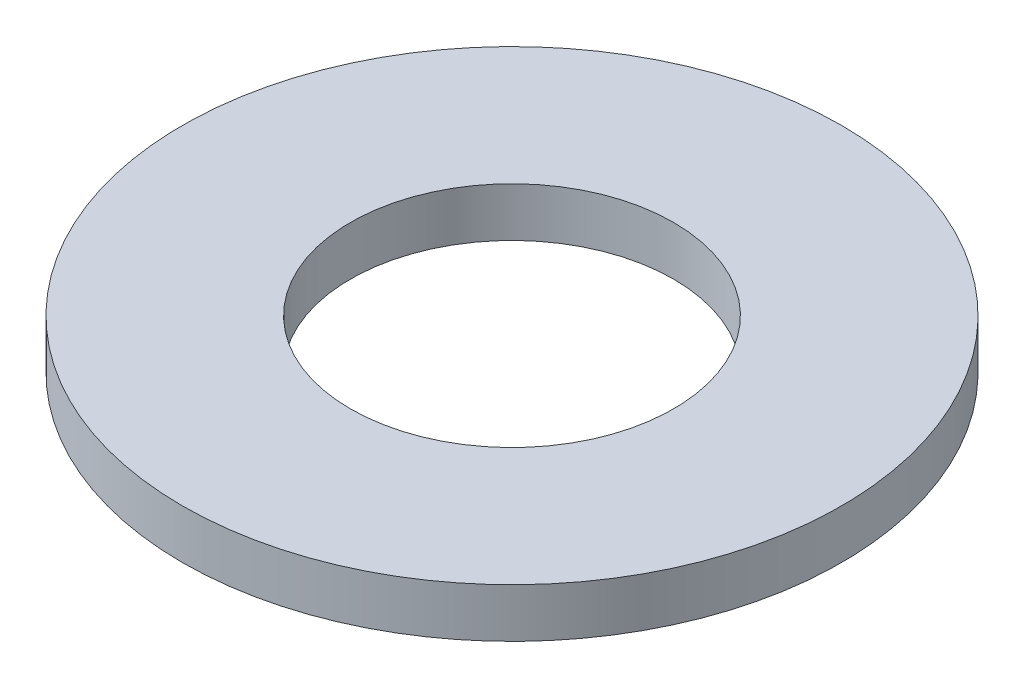
SolidWorks part; units mm, degrees
ref_plane "Front Plane" through (0, 0, 0) normal (0, 0, 1) x (1, 0, 0)
ref_plane "Top Plane" through (0, 0, 0) normal (0, 1, 0) x (1, 0, 0)
ref_plane "Right Plane" through (0, 0, 0) normal (1, 0, 0) x (0, 0, -1)
sketch "Sketch1" plane through (0, 0, 0) normal (0, 1, 0) x (1, 0, 0)
  circle A0 centre (0, 0) radius 3.2385
  dimension "OD" = 6.477
extrude "Boss-Extrude1" add sketch "Sketch1" along normal blind 0.4826
sketch "Sketch5" plane through (0, 0.4826, 0) normal (0, 1, 0) x (-1, 0, 0)
  circle A0 centre (0, 0) radius 1.5875
  dimension "ID" = 3.175
extrude "Cut-Extrude1" cut sketch "Sketch5" against normal through all
